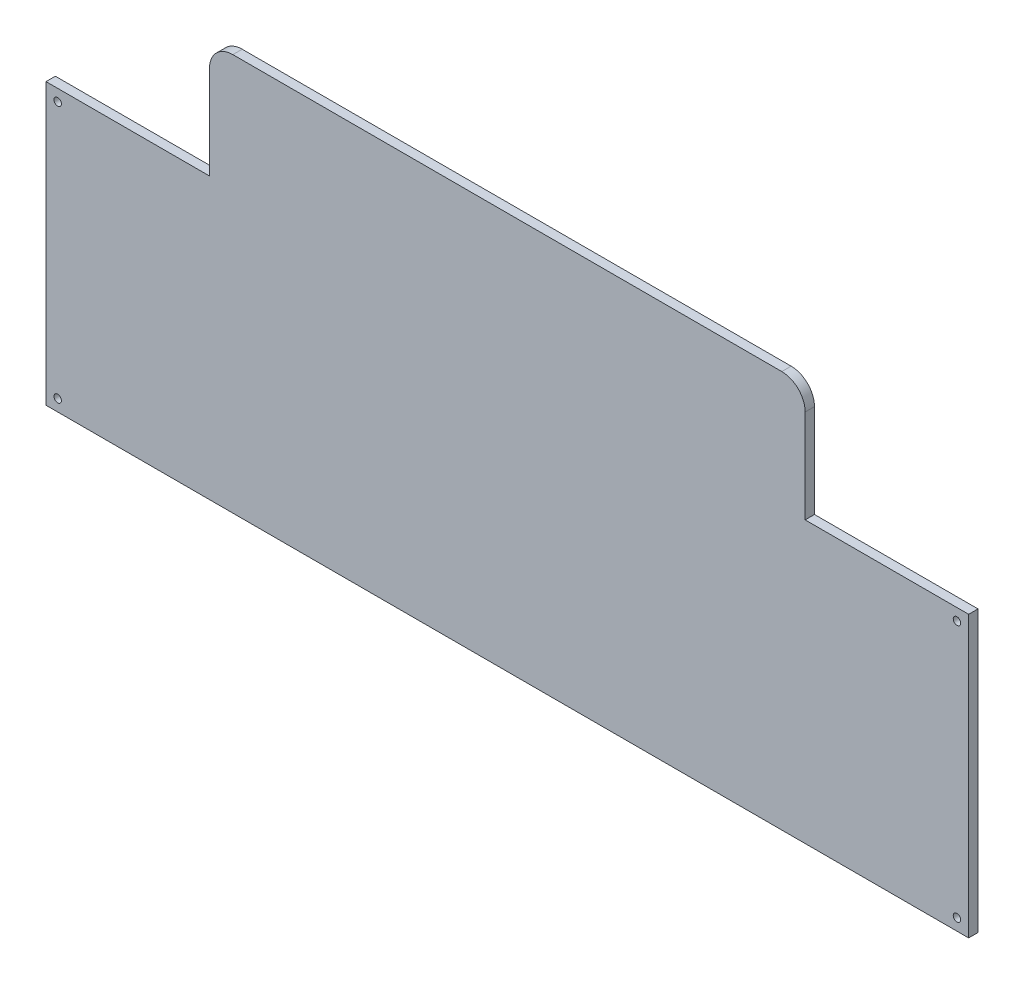
SolidWorks part; units mm, degrees
ref_plane "前视基准面" through (0, 0, 0) normal (0, 0, 1) x (1, 0, 0)
ref_plane "上视基准面" through (0, 0, 0) normal (0, 1, 0) x (1, 0, 0)
ref_plane "右视基准面" through (0, 0, 0) normal (1, 0, 0) x (0, 0, -1)
other "Configuration Table"
sketch "草图1" plane through (0, 0, 0) normal (0, 0, 1) x (1, 0, 0)
  line L0 (0, 0) -> (0, 94.204) construction
  line L1 (-197.5, 60) -> (-127.5, 60)
  line L2 (-197.5, 60) -> (-197.5, -60)
  line L3 (-197.5, -60) -> (197.5, -60)
  line L4 (197.5, 60) -> (197.5, -60)
  line L5 (-197.5, 60) -> (197.5, -60) construction
  line L6 (-197.5, -60) -> (197.5, 60) construction
  line L7 (0, 0) -> (100.4934, 0) construction
  line L8 (-127.5, 60) -> (-127.5, 100)
  line L9 (-117.5, 110) -> (117.5, 110)
  line L10 (127.5, 100) -> (127.5, 60)
  line L11 (127.5, 60) -> (197.5, 60)
  circle A0 centre (-192.5, 55) radius 1.6
  circle A1 centre (192.5, 55) radius 1.6
  circle A2 centre (192.5, -55) radius 1.6
  circle A3 centre (-192.5, -55) radius 1.6
  arc A4 (117.5, 110) -> (127.5, 100) centre (117.5, 100) cw
  arc A5 (-127.5, 100) -> (-117.5, 110) centre (-117.5, 100) cw
  point P0 (0, 0)
  point P19 (0, 110)
  point P24 (127.5, 110)
  point P27 (-127.5, 110)
  dimension "D3" = 3.2
  dimension "D8" = 10
  dimension "D1" = 395
  dimension "D2" = 120
  dimension "D4" = 5
  dimension "D5" = 5
  dimension "D6" = 255
  dimension "D7" = 50
extrude "凸台-拉伸1" add sketch "草图1" along normal blind 4
